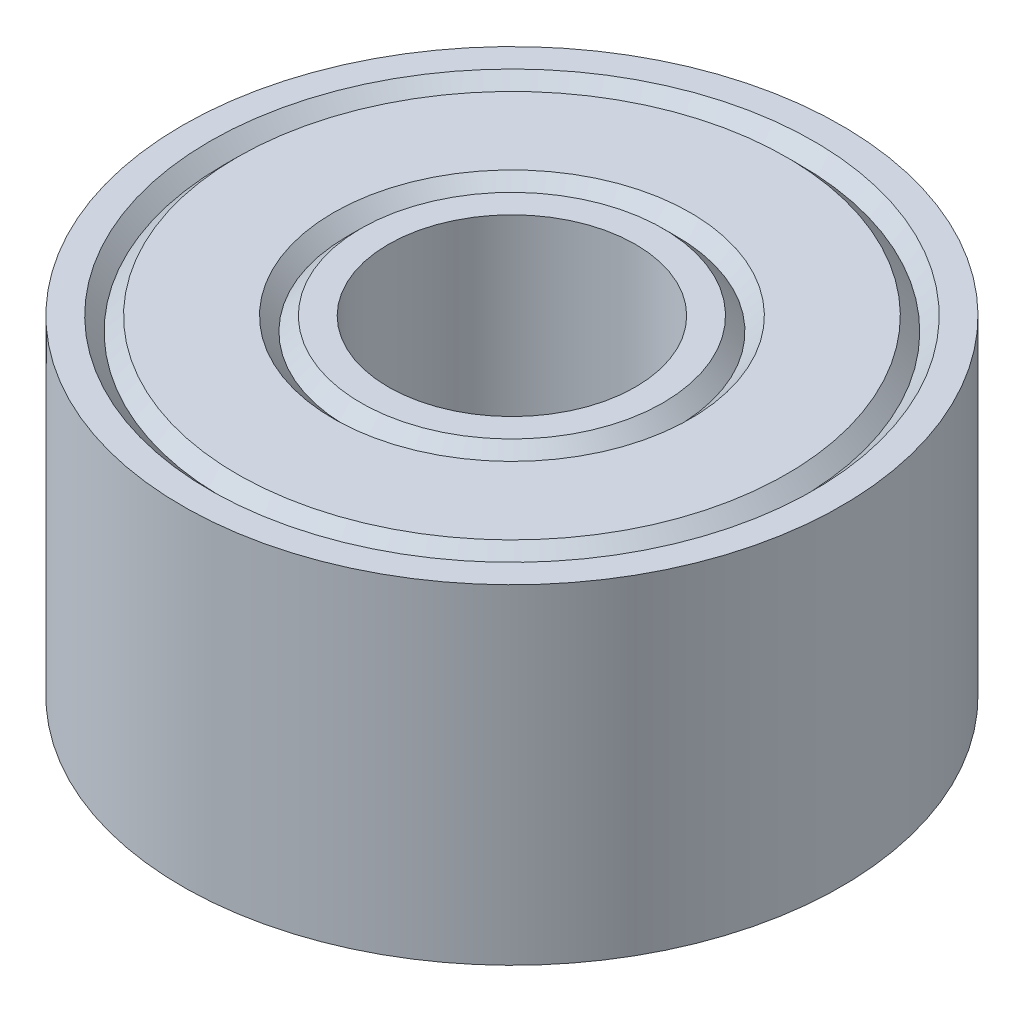
SolidWorks part; units mm, degrees
ref_plane "Front Plane" through (0, 0, 0) normal (0, 0, 1) x (1, 0, 0)
ref_plane "Top Plane" through (0, 0, 0) normal (0, 1, 0) x (1, 0, 0)
ref_plane "Right Plane" through (0, 0, 0) normal (1, 0, 0) x (0, 0, -1)
sketch "Sketch1" plane through (0, 0, 0) normal (0, 0, 1) x (1, 0, 0)
  line L0 (0, 2) -> (0, -2) construction
  line L1 (-1.5, 2) -> (-1.8333, 2)
  line L2 (-1.5, 2) -> (-1.5, -2)
  line L3 (-1.5, -2) -> (-1.8333, -2)
  line L4 (-4, 2) -> (-4, -2)
  line L5 (-3.6667, 2) -> (-3.5, 1.8333)
  line L6 (-3.5, 1.8333) -> (-3.3333, 2)
  line L7 (-2.1667, 2) -> (-2, 1.8333)
  line L8 (-2, 1.8333) -> (-1.8333, 2)
  line L9 (-3.6667, -2) -> (-3.5, -1.8333)
  line L10 (-3.5, -1.8333) -> (-3.3333, -2)
  line L11 (-2.1667, -2) -> (-2, -1.8333)
  line L12 (-2, -1.8333) -> (-1.8333, -2)
  line L13 (-2.1667, -2) -> (-3.3333, -2)
  line L14 (-3.6667, -2) -> (-4, -2)
  line L15 (-3.6667, 2) -> (-4, 2)
  line L16 (-2.1667, 2) -> (-3.3333, 2)
  line L17 (-3.5, 1.8333) -> (-2, 1.8333) construction
  line L18 (-3.5, 1.8333) -> (-3.5, -1.8333) construction
  line L19 (-2, -1.8333) -> (-3.5, -1.8333) construction
  line L20 (-2, 1.8333) -> (-2, -1.8333) construction
  line L21 (-3.5, 0) -> (-3, 0) construction
  line L22 (-1.8333, 2) -> (-2.1667, 2) construction
  line L23 (-3, 0) -> (-2.5, 0) construction
  line L24 (-3.5, 0) -> (-4, 0) construction
  line L25 (-2.5, 0) -> (-2, 0) construction
  line L26 (-2, 0) -> (-1.5, 0) construction
  dimension "D1" = 4
  dimension "D2" = 3
  dimension "D3" = 8
revolve "Revolve1" add sketch "Sketch1" angle 360 about L0
